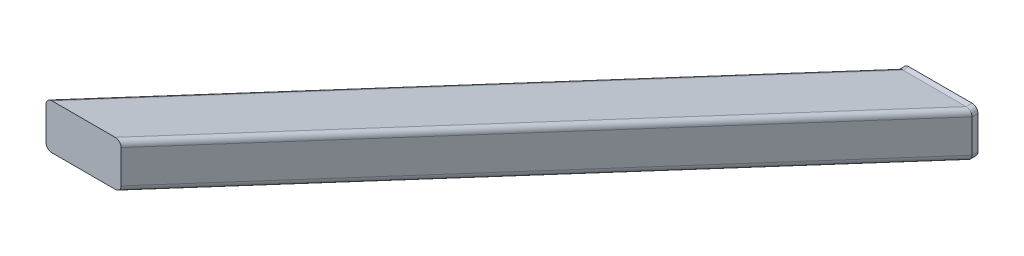
SolidWorks part; units mm, degrees
ref_plane "Alzado" through (0, 0, 0) normal (0, 0, 1) x (1, 0, 0)
ref_plane "Planta" through (0, 0, 0) normal (0, 1, 0) x (1, 0, 0)
ref_plane "Vista lateral" through (0, 0, 0) normal (1, 0, 0) x (0, 0, -1)
sketch "Croquis1" plane through (0, 0, 0) normal (0, 0, 1) x (1, 0, 0)
  line L1 (10, 0) -> (117, 0)
  line L2 (0, -10) -> (0, -66.2)
  line L3 (10, -76.2) -> (117, -76.2)
  line L4 (127, -10) -> (127, -66.2)
  arc A0 (0, -66.2) -> (10, -76.2) centre (10, -66.2) ccw
  arc A1 (117, -76.2) -> (127, -66.2) centre (117, -66.2) ccw
  arc A2 (117, 0) -> (127, -10) centre (117, -10) cw
  arc A3 (10, 0) -> (0, -10) centre (10, -10) ccw
  point P7 (0, -76.2)
  point P12 (127, 0)
  point P15 (0, 0)
  dimension "D3" = 10
  dimension "D1" = 127
  dimension "D2" = 76.2
extrude "Saliente-Extruir1" add sketch "Croquis1" along normal blind 10
sketch3d "Croquis3D1"
  line L0 (63.5, 0, 10) -> (63.5, -76.2, 10) construction
  line L1 (117, 0, 10) -> (10, 0, 10) construction
  line L2 (10, -76.2, 10) -> (117, -76.2, 10) construction
  line L3 (63.5, -38.1, 10) -> (63.5, -38.1, 1000) construction
  line L6 (63.5, -38.1, 1000) -> (-386.5, -38.1, 1000) construction
  line L7 (-386.5, -38.1, 1000) -> (-386.5, 186.9, 1000) construction
  line L9 (-386.5, 186.9, 1000) -> (63.5, -38.1, 10)
  dimension "D1" = 990
  dimension "D2" = 450
  dimension "D3" = 225
sketch "Croquis2" plane through (0, 0, 10) normal (0, 0, 1) x (1, 0, 0)
  line L1 (10, -76.2) -> (117, -76.2)
  line L2 (0, -66.2) -> (0, -10)
  line L3 (10, 0) -> (117, 0)
  line L4 (127, -66.2) -> (127, -10)
  line L5 (0, -76.2) -> (127, 0) construction
  line L6 (0, 0) -> (127, -76.2) construction
  arc A0 (10, -76.2) -> (0, -66.2) centre (10, -66.2) cw
  arc A1 (117, -76.2) -> (127, -66.2) centre (117, -66.2) ccw
  arc A2 (117, 0) -> (127, -10) centre (117, -10) cw
  arc A3 (0, -10) -> (10, 0) centre (10, -10) cw
  point P0 (63.5, -38.1)
  dimension "D1" = 10
sweep "Barrer1" add profiles "Croquis2" path "Croquis3D1"
